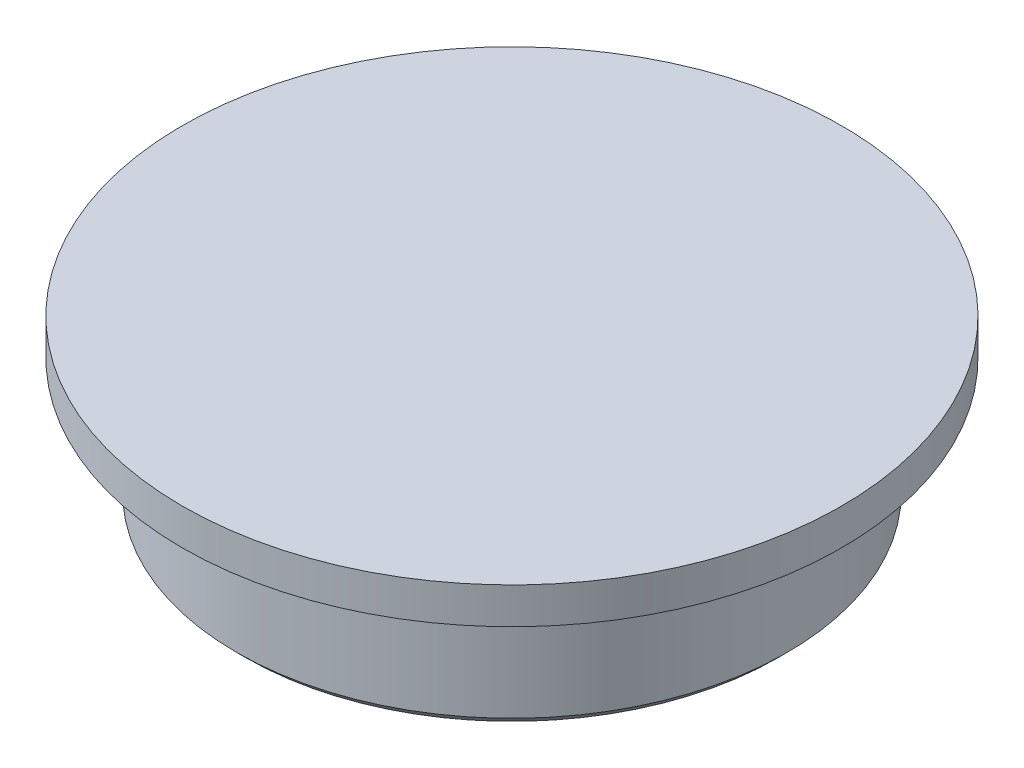
SolidWorks part; units mm, degrees
ref_plane "정면" through (0, 0, 0) normal (0, 0, 1) x (1, 0, 0)
ref_plane "윗면" through (0, 0, 0) normal (0, 1, 0) x (1, 0, 0)
ref_plane "우측면" through (0, 0, 0) normal (1, 0, 0) x (0, 0, -1)
sketch "스케치1" plane through (0, 0, 0) normal (0, 1, 0) x (1, 0, 0)
  circle A0 centre (0, 0) radius 15.2
  dimension "D1" = 30.4
extrude "D30.4t7" add sketch "스케치1" along normal blind 7
sketch "스케치2" plane through (0, 7, 0) normal (0, 1, 0) x (1, 0, 0)
  circle A0 centre (0, 0) radius 18.2
  circle A1 centre (0, 0) radius 15.2 construction
  circle A2 centre (0, 0) radius 15.2
  circle M3 centre (0, 0) radius 15.2
  dimension "D1" = 3
extrude "보스-돌출2" add sketch "스케치2" along normal blind 2 contours M3 | A0 M3 | A2
sketch "스케치3" plane through (0, 0, 0) normal (0, -1, 0) x (1, 0, 0)
  circle A0 centre (0, 0) radius 13.2
  circle A1 centre (0, 0) radius 15.2
  circle A2 centre (0, 0) radius 15.2
  dimension "D2" = 2
  dimension "D1" = 0
extrude "컷-돌출1" cut sketch "스케치3" against normal blind 7 contours A0
chamfer "모따기1" distance 0.5 angle 45 1 edges at (0, 0, 15.2)
